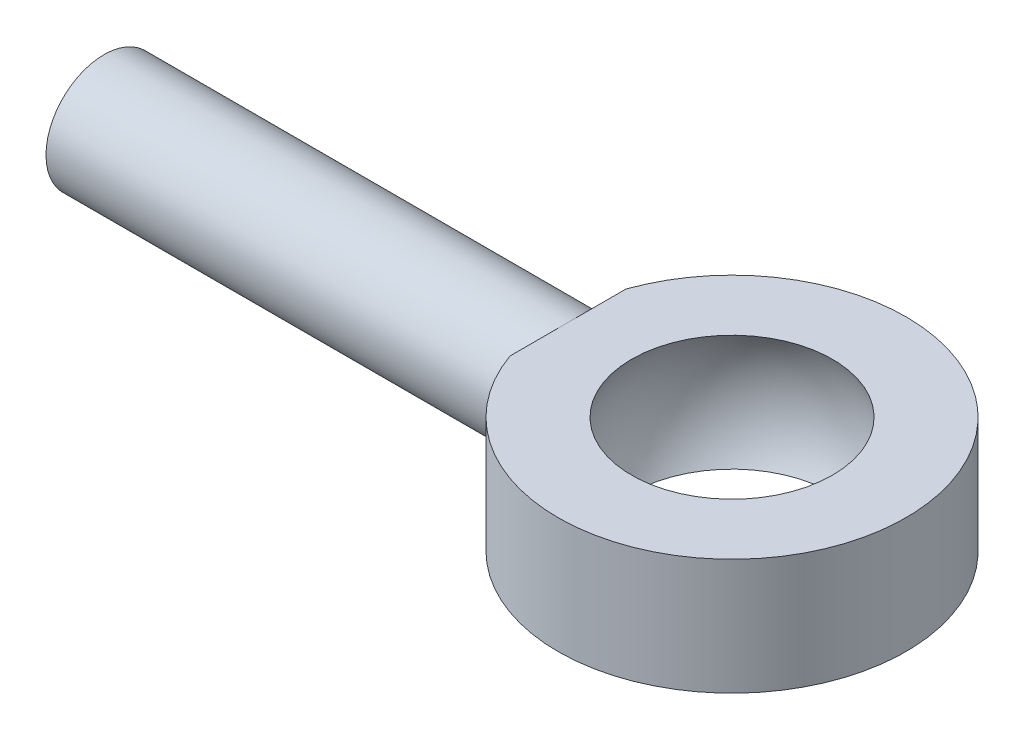
SolidWorks part; units mm, degrees
ref_plane "Front Plane" through (0, 0, 0) normal (0, 0, 1) x (1, 0, 0)
ref_plane "Top Plane" through (0, 0, 0) normal (0, 1, 0) x (1, 0, 0)
ref_plane "Right Plane" through (0, 0, 0) normal (1, 0, 0) x (0, 0, -1)
sketch "Sketch1" plane through (0, 0, 0) normal (0, 1, 0) x (1, 0, 0)
  line L0 (-8.9803, 3.175) -> (-8.9803, -3.175)
  arc A0 (-8.9803, 3.175) -> (-8.9803, -3.175) centre (0, 0) cw
  dimension "D1" = 9.525
  dimension "D2" = 6.35
extrude "Boss-Extrude1" add sketch "Sketch1" along normal blind 6.35
sketch "Sketch2" plane through (-8.9803, 0, 0) normal (-1, 0, 0) x (0, 0, 1)
  line L0 (-3.175, 6.35) -> (3.175, 0) construction
  circle A0 centre (0, 3.175) radius 3.175
  dimension "D1" = 6.35
extrude "Boss-Extrude2" add sketch "Sketch2" along normal blind 25.4
sketch "Sketch3" plane through (0, 0, 0) normal (0, 0, 1) x (1, 0, 0)
  line L0 (0, 9.525) -> (0, -3.175)
  line L1 (0, 6.35) -> (0, 0) construction
  line L2 (9.525, 6.35) -> (-8.9803, 6.35) construction
  line L3 (-8.9803, 0) -> (9.525, 0) construction
  arc A0 (0, 9.525) -> (0, -3.175) centre (0, 3.175) cw
  dimension "D1" = 12.7
revolve "Cut-Revolve1" cut sketch "Sketch3" angle 360 about L1
